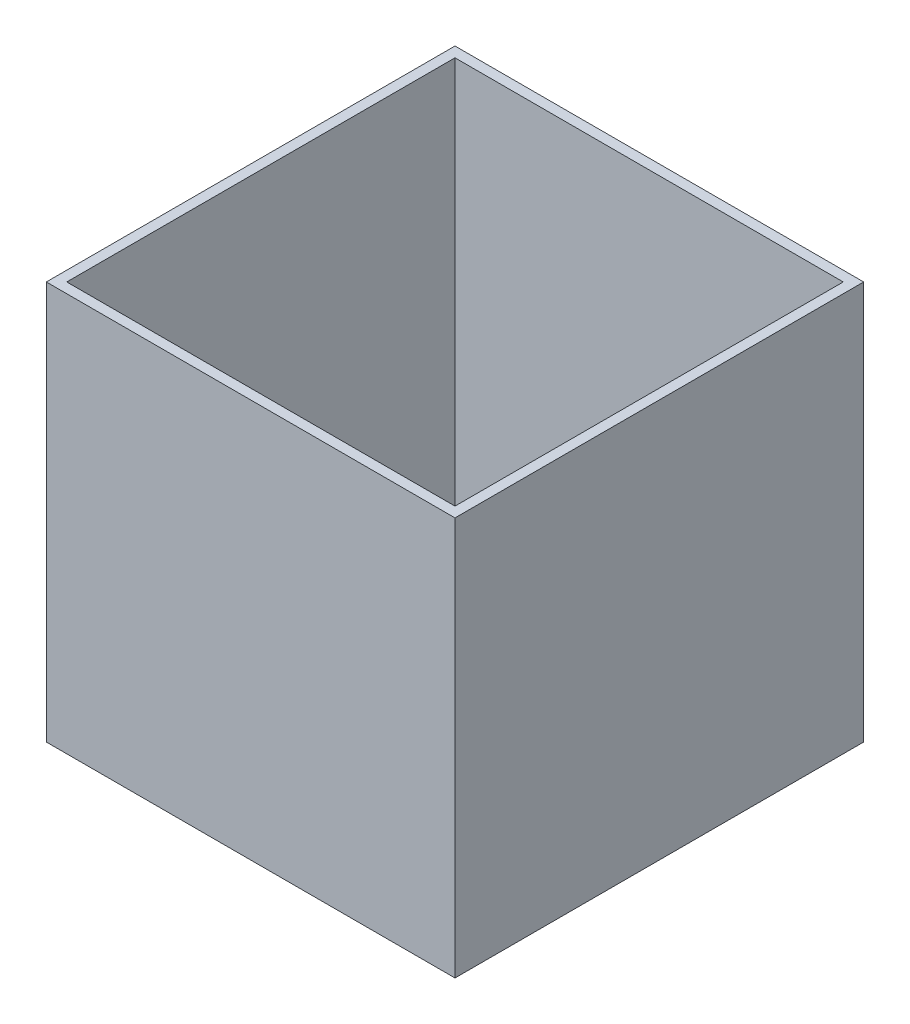
SolidWorks part; units mm, degrees
ref_plane "Front Plane" through (0, 0, 0) normal (0, 0, 1) x (1, 0, 0)
ref_plane "Top Plane" through (0, 0, 0) normal (0, 1, 0) x (1, 0, 0)
ref_plane "Right Plane" through (0, 0, 0) normal (1, 0, 0) x (0, 0, -1)
sketch "Sketch1" plane through (0, 0, 0) normal (0, 1, 0) x (1, 0, 0)
  line L1 (-40, 40) -> (40, 40)
  line L2 (-40, 40) -> (-40, -40)
  line L3 (-40, -40) -> (40, -40)
  line L4 (40, 40) -> (40, -40)
  line L5 (-40, 40) -> (40, -40) construction
  line L6 (-40, -40) -> (40, 40) construction
  circle A0 centre (0, 0) radius 18.4
  point P0 (0, 0)
  dimension "D3" = 36.8
  dimension "D1" = 80
  dimension "D2" = 80
extrude "Boss-Extrude1" add sketch "Sketch1" along normal blind 2
sketch "Sketch2" plane through (0, 2, 0) normal (0, 1, 0) x (1, 0, 0)
  line L1 (40, -40) -> (44, -40)
  line L2 (40, -40) -> (40, -21.5)
  line L3 (40, -21.5) -> (44, -21.5)
  line L4 (44, -40) -> (44, -21.5)
  dimension "D1" = 18.5
  dimension "D2" = 4
extrude "Boss-Extrude2" add sketch "Sketch2" against normal blind 15.25
sketch "Sketch3" plane through (44, 0, 0) normal (1, 0, 0) x (0, 0, -1)
  line L1 (-40, -13.25) -> (-21.5, -13.25) construction
  line L4 (-40, -13.25) -> (-40, 2) construction
  circle A0 centre (-30.75, -8.125) radius 2.2
  dimension "D1" = 4.4
  dimension "D2" = 5.125
  dimension "D3" = 9.25
extrude "Cut-Extrude1" cut sketch "Sketch3" against normal through all
ref_plane "Plane1" through (0, 0, 0) normal (1, 0, 0) x (0, 0, -1)
mirror "Mirror1" about plane through (0, 0, 0) normal (1, 0, 0) of "Cut-Extrude1", "Boss-Extrude2"
ref_plane "Plane2" through (0, 0, 0) normal (0, 0, -1) x (-1, 0, 0)
mirror "Mirror2" about plane through (0, 0, 0) normal (0, 0, -1) of "Mirror1", "Cut-Extrude1", "Boss-Extrude2"
sketch "Sketch4" plane through (0, 2, 0) normal (0, 1, 0) x (1, 0, 0)
  line L1 (44, 40) -> (-44, 40) construction
  line L2 (-40, 21.5) -> (-40, -21.5) construction
  circle A1 centre (-24, 24) radius 2.2
  circle A4 centre (24, 24) radius 2.2
  dimension "D1" = 16
  dimension "D2" = 16
  dimension "D3" = 2
extrude "Cut-Extrude2" cut sketch "Sketch4" against normal through all
mirror "Mirror3" about plane through (0, 0, 0) normal (0, 0, -1) of "Cut-Extrude2"
sketch "Sketch5" plane through (0, 0, 40) normal (0, 0, 1) x (1, 0, 0)
  line L1 (-40, -13.25) -> (-44, -13.25)
  line L2 (-40, -13.25) -> (-40, 2)
  line L3 (-40, 2) -> (-44, 2)
  line L4 (-44, -13.25) -> (-44, 2)
  line L5 (40, -13.25) -> (44, -13.25)
  line L6 (40, -13.25) -> (40, 2)
  line L7 (40, 2) -> (44, 2)
  line L8 (44, -13.25) -> (44, 2)
extrude "Cut-Extrude3" cut sketch "Sketch5" against normal through all
sketch "Sketch6" plane through (0, 2, 0) normal (0, 1, 0) x (1, 0, 0)
  line L1 (-40, 40) -> (40, 40)
  line L2 (-40, 40) -> (-40, -40)
  line L3 (-40, -40) -> (40, -40)
  line L4 (40, 40) -> (40, -40)
  line L5 (38, 38) -> (-38, 38)
  line L6 (38, 38) -> (38, -38)
  line L7 (38, -38) -> (-38, -38)
  line L8 (-38, 38) -> (-38, -38)
  line L9 (38, 38) -> (-38, -38) construction
  line L10 (38, -38) -> (-38, 38) construction
  point P6 (0, 0)
  dimension "D1" = 76
  dimension "D2" = 76
extrude "Boss-Extrude3" add sketch "Sketch6" along normal blind 76
